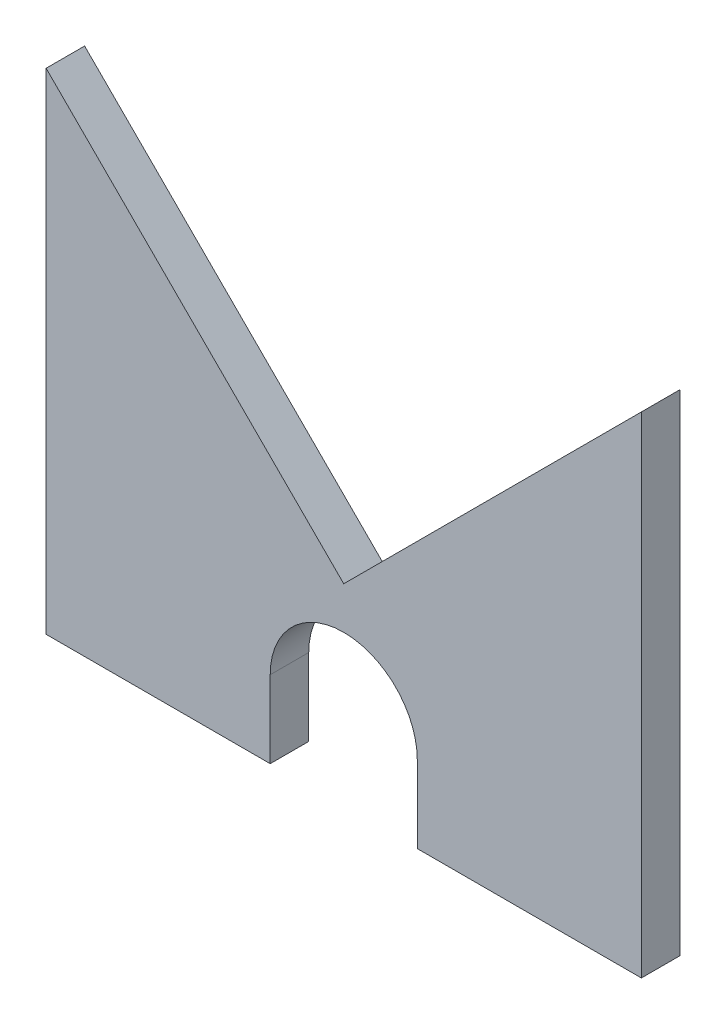
SolidWorks part; units mm, degrees
ref_plane "Front Plane" through (0, 0, 0) normal (0, 0, 1) x (1, 0, 0)
ref_plane "Top Plane" through (0, 0, 0) normal (0, 1, 0) x (1, 0, 0)
ref_plane "Right Plane" through (0, 0, 0) normal (1, 0, 0) x (0, 0, -1)
sketch "Sketch1" plane through (0, 0, 0) normal (0, 0, 1) x (1, 0, 0)
  line L0 (0, 28) -> (17, 11)
  line L1 (0, 0) -> (34, 0)
  line L2 (0, 0) -> (0, 28)
  line L3 (0, 28) -> (34, 28)
  line L4 (34, 0) -> (34, 28)
  line L5 (17, 11) -> (34, 28)
  line L6 (17, 0) -> (17, 7.9307) construction
  line L7 (12.8, 4.4) -> (12.8, 0)
  line L8 (21.2, 4.4) -> (21.2, 0)
  circle A0 centre (17, 4.4) radius 4.2
  dimension "D5" = 8.4
  dimension "D1" = 28
  dimension "D2" = 34
  dimension "D3" = 45
  dimension "D4" = 45
  dimension "D6" = 4.4
extrude "Boss-Extrude1" add sketch "Sketch1" along normal blind 2.2 contours A0 L8 L1 L4 L5 L0 L2 L7
